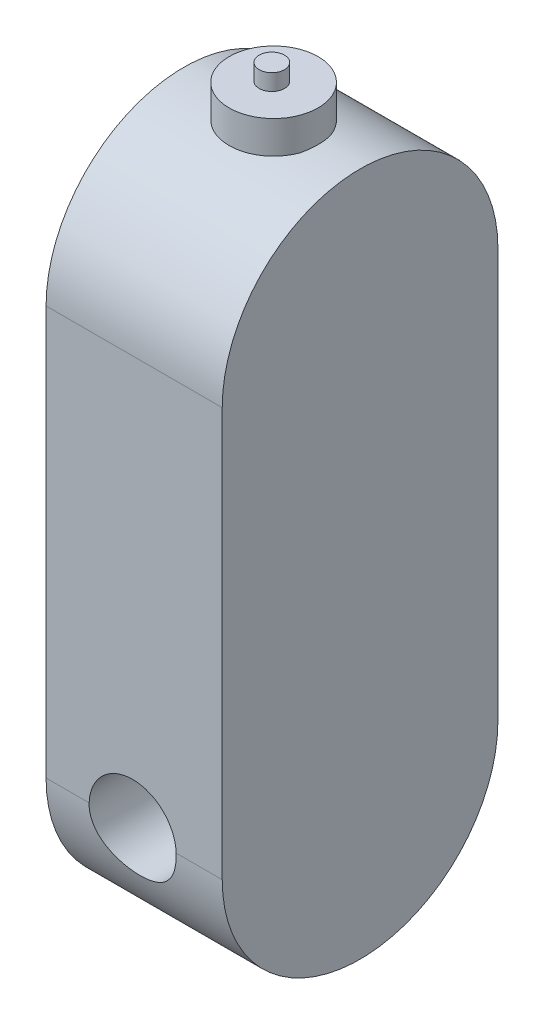
SolidWorks part; units mm, degrees
ref_plane "Front Plane" through (0, 0, 0) normal (0, 0, 1) x (1, 0, 0)
ref_plane "Top Plane" through (0, 0, 0) normal (0, 1, 0) x (1, 0, 0)
ref_plane "Right Plane" through (0, 0, 0) normal (1, 0, 0) x (0, 0, -1)
sketch "Sketch3" plane through (0, 0, 0) normal (1, 0, 0) x (0, 0, -1)
  line L0 (0, -21.6636) -> (0, 41.0001) construction
  line L1 (-21.1295, -21.6636) -> (-21.1295, 41.0001)
  line L2 (21.1295, -21.6636) -> (21.1295, 41.0001)
  arc A0 (-21.1295, -21.6636) -> (21.1295, -21.6636) centre (0, -21.6636) ccw
  arc A1 (21.1295, 41.0001) -> (-21.1295, 41.0001) centre (0, 41.0001) ccw
  point P3 (0, 9.6683)
  dimension "D1" = 62.6636
extrude "Boss-Extrude2" add sketch "Sketch3" along normal blind 27
ref_plane "Plane1" through (0, 0, 22) normal (0, 0, 1) x (1, 0, 0)
sketch "Sketch6" plane through (0, 0, 22) normal (0, 0, 1) x (1, 0, 0)
  circle A0 centre (13.273, -21.8784) radius 6.6749
  point P2 (0, 0)
extrude "Cut-Extrude4" cut sketch "Sketch6" against normal blind 51
ref_plane "Plane2" through (0, 62, 0) normal (0, 1, 0) x (1, 0, 0)
sketch "Sketch7" plane through (0, 62, 0) normal (0, 1, 0) x (1, 0, 0)
  circle A0 centre (13.7471, 0) radius 6.8176
extrude "Boss-Extrude3" add sketch "Sketch7" along normal blind 5
sketch "Sketch8" plane through (0, 67, 0) normal (0, 1, 0) x (1, 0, 0)
  circle A0 centre (13.4728, 0) radius 1.9369
extrude "Boss-Extrude4" add sketch "Sketch8" along normal blind 2.5
